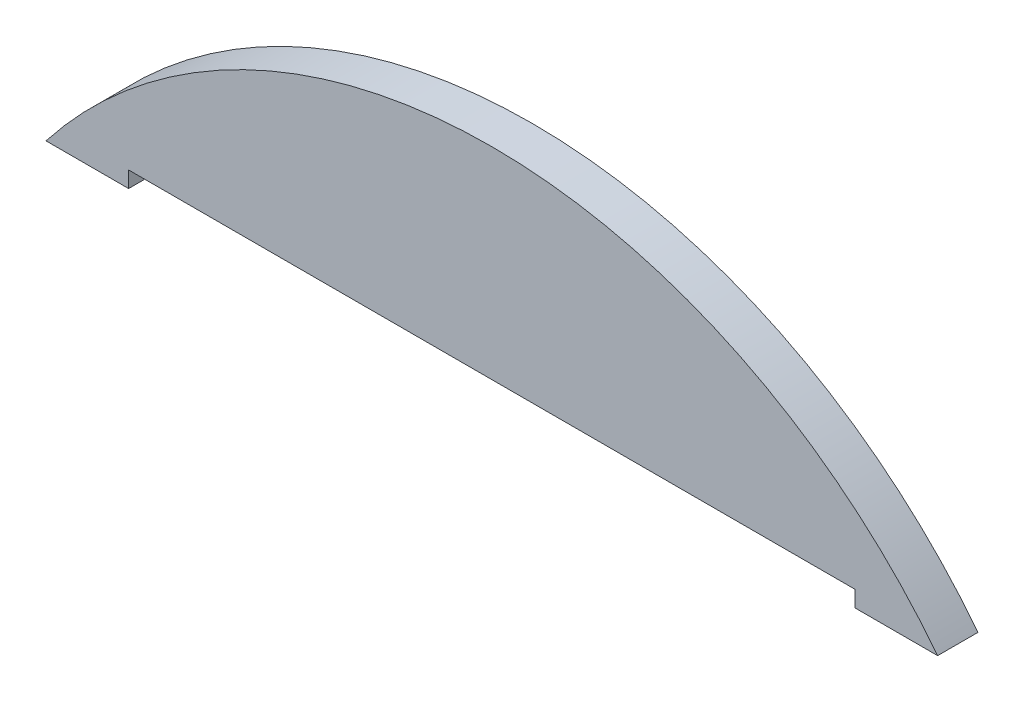
SolidWorks part; units mm, degrees
material "Balsa"
ref_plane "Plan de face" through (0, 0, 0) normal (0, 0, 1) x (1, 0, 0)
ref_plane "Plan de dessus" through (0, 0, 0) normal (0, 1, 0) x (1, 0, 0)
ref_plane "Plan de droite" through (0, 0, 0) normal (1, 0, 0) x (0, 0, -1)
sketch "Esquisse1" plane through (0, 0, 0) normal (0, 0, 1) x (1, 0, 0)
  line L0 (45, 45) -> (45, -45)
  line L1 (45, -45) -> (-45, -45)
  line L2 (-45, -45) -> (-45, 45)
  line L3 (-45, 45) -> (45, 45)
  line L8 (45, -45) -> (-45, 45) construction
  line L9 (-45, -45) -> (45, 45) construction
  circle A0 centre (0, 0) radius 175
  dimension "D2" = 350
  dimension "D3" = 90
  dimension "D1" = 90
extrude "Boss.-Extru.1" add sketch "Esquisse1" along normal blind 5
sketch "Esquisse2" plane through (0, 0, 5) normal (0, 0, 1) x (1, 0, 0)
  line L0 (-90, 0) -> (-49.5717, 0) construction
  line L1 (-156.4682, 78.3754) -> (-90, 40)
  line L2 (0, 0) -> (0, 175) construction
  line L3 (-90, 40) -> (-90, -40)
  line L4 (-90, -40) -> (-156.4682, -78.3754)
  circle A0 centre (0, 0) radius 175 construction
  arc A1 (-156.4682, 78.3754) -> (-156.4682, -78.3754) centre (0, 0) ccw
  dimension "D2" = 80
  dimension "D1" = 90
  dimension "D3" = 90
  dimension "D4" = 120
extrude "Enlèv. mat.-Extru.1" cut sketch "Esquisse2" against normal blind 10
sketch "Esquisse3" plane through (0, 0, 5) normal (0, 0, 1) x (1, 0, 0)
  line L0 (-156.4682, 78.3754) -> (-95.1962, 43)
  line L1 (-200, 43) -> (-95.1962, 43)
  line L2 (-200, 43) -> (-200, -207)
  line L3 (-200, -207) -> (200, -207)
  line L4 (200, 43) -> (200, -207)
  line L5 (45, 45) -> (-45, 45) construction
  line L6 (-90, 40) -> (-156.4682, 78.3754) construction
  line L7 (-55.2359, 43) -> (55.2359, 43)
  line L8 (169.6349, 43) -> (200, 43)
  arc A0 (-55.2359, 43) -> (55.2359, 43) centre (0, 0) cw
  arc A1 (169.6349, 43) -> (-156.4682, 78.3754) centre (0, 0) ccw
  arc A2 (-156.4682, -78.3754) -> (-156.4682, 78.3754) centre (0, 0) ccw construction
  dimension "D5" = 70
  dimension "D1" = 400
  dimension "D2" = 200
  dimension "D3" = 250
  dimension "D4" = 2
extrude "Enlèv. mat.-Extru.4" cut sketch "Esquisse3" against normal blind 10
